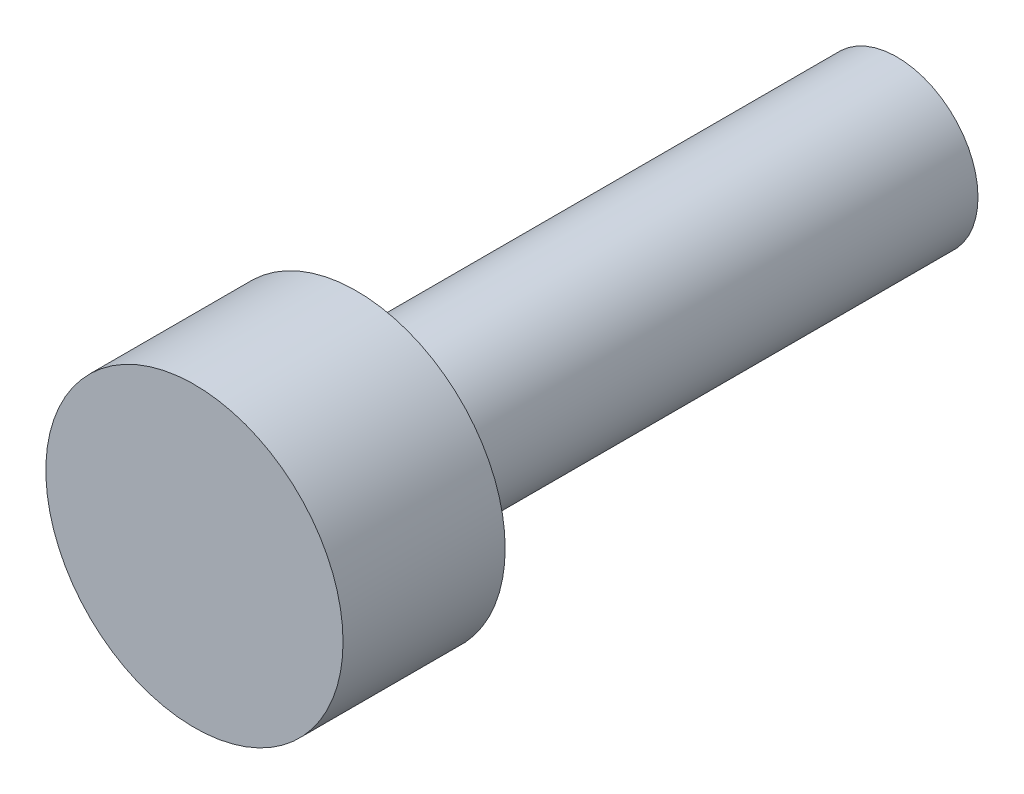
SolidWorks part; units mm, degrees
ref_plane "前视基准面" through (0, 0, 0) normal (0, 0, 1) x (1, 0, 0)
ref_plane "上视基准面" through (0, 0, 0) normal (0, 1, 0) x (1, 0, 0)
ref_plane "右视基准面" through (0, 0, 0) normal (1, 0, 0) x (0, 0, -1)
other "Configuration Table"
sketch "草图1" plane through (0, 0, 0) normal (0, 0, 1) x (1, 0, 0)
  circle A0 centre (0, 0) radius 1.5
extrude "M3x10螺杆" add sketch "草图1" along normal blind 10
sketch "草图2" plane through (0, 0, 0) normal (0, 0, 1) x (1, 0, 0)
  circle A0 centre (0, 0) radius 2.75
extrude "螺钉头" add sketch "草图2" along normal blind 3 from offset 10
